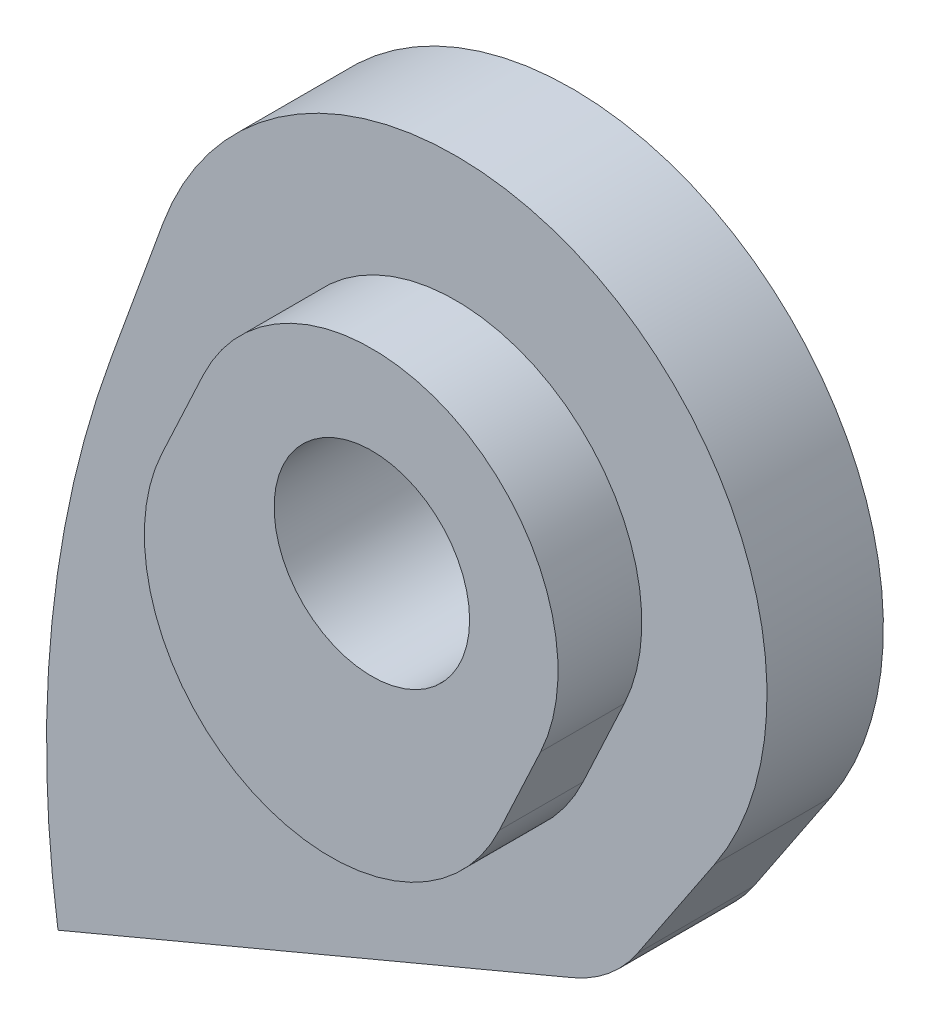
SolidWorks part; units mm, degrees
ref_plane "Front Plane" through (0, 0, 0) normal (0, 0, 1) x (1, 0, 0)
ref_plane "Top Plane" through (0, 0, 0) normal (0, 1, 0) x (1, 0, 0)
ref_plane "Right Plane" through (0, 0, 0) normal (1, 0, 0) x (0, 0, -1)
sketch "Sketch6" plane through (0, 0, 0) normal (0, 0, 1) x (1, 0, 0)
  line L0 (0, 0) -> (40.1809, 0) construction
  line L1 (0, 0) -> (35.507, 92.499) construction
  line L2 (19.3519, 50.4133) -> (0.4719, 63.0164) construction
  line L3 (19.3519, 50.4133) -> (-36.1025, 71.7003) construction
  dimension "D1" = 69
  dimension "D2" = 54
  dimension "D3" = 22.7
  dimension "D4" = 5
sketch "Sketch3" plane through (0, 0, 0) normal (0, 0, 1) x (1, 0, 0)
  line L0 (24.1743, 72.523) -> (120.8717, 72.523) construction
  line L6 (11.8164, 60.2529) -> (11.7284, 60.3116)
  line L7 (7.3748, 53.5992) -> (5.9136, 54.5745)
  line L8 (19.3519, 50.4133) -> (0.4719, 63.0164) construction
  line L9 (-6.1719, 82.4206) -> (-7.2903, 79.3479)
  line L10 (19.3519, 50.4133) -> (13.2479, 41.2693) construction
  line L11 (19.3519, 50.4133) -> (31.6629, 68.8558) construction
  line L12 (4.0204, 73.9337) -> (5.6789, 76.4182)
  line L14 (0.1147, 80.1325) -> (27.1455, 62.0885) construction
  line L15 (0.1147, 80.1325) -> (-7.2903, 79.3479) construction
  line L16 (0.1147, 80.1325) -> (0.1147, 91.1913) construction
  line L17 (0.1147, 80.1325) -> (-6.1719, 82.4206) construction
  arc A0 (13.4996, 47.0498) -> (20.2139, 57.1081) centre (19.3519, 50.4133) ccw
  arc A1 (20.2139, 57.1081) -> (11.8164, 60.2529) centre (22.7223, 76.5904) cw
  arc A2 (13.4996, 47.0498) -> (7.3748, 53.5992) centre (-3.5311, 37.2616) ccw
  arc A3 (11.7284, 60.3116) -> (6.8662, 65.9311) centre (19.4923, 71.9424) cw
  arc A4 (-6.1719, 82.4206) -> (5.6789, 76.4182) centre (0.1147, 80.1325) cw
  arc A5 (6.8662, 65.9311) -> (4.9012, 68.3908) centre (0.6246, 62.9595) ccw
  arc A6 (4.9012, 68.3908) -> (4.0204, 73.9337) centre (7.4585, 71.6386) cw
  arc A7 (5.9136, 54.5745) -> (0.4148, 56.2666) centre (0.3298, 46.2096) ccw
  arc A10 (0.4148, 56.2666) -> (-5.2798, 59.4837) centre (0.4719, 63.0164) cw
  circle A12 centre (19.3519, 50.4133) radius 2.75
  circle A13 centre (0.4719, 63.0164) radius 2.75
  circle A17 centre (0.1147, 80.1325) radius 2.1
  arc A18 (-7.2903, 79.3479) -> (-5.2798, 59.4837) centre (14.2795, 71.4971) ccw
  dimension "D1" = 5.5
  dimension "D2" = 5.5
  dimension "D3" = 4
  dimension "D5" = 4
  dimension "D6" = 4
  dimension "D4" = 4.2
  dimension "D17" = 70
  dimension "D18" = 3.27
  dimension "D14" = 6.69
  dimension "D7" = 3
  dimension "D8" = 4
  dimension "D9" = 3
  dimension "D10" = 4
  dimension "D11" = 19
  dimension "D12" = 19
  dimension "D13" = 22
  dimension "D15" = 32.5
  dimension "D16" = 14
extrude "Boss-Extrude2" add sketch "Sketch3" along normal blind 11
sketch "Sketch13" plane through (0, 0, 0) normal (0, 0, -1) x (-1, 0, 0)
  line L0 (-5.6789, 76.4182) -> (-4.0204, 73.9337)
  line L1 (-2.6258, 72.7829) -> (8.4277, 68.1397)
  line L2 (6.1719, 82.4206) -> (7.2903, 79.3479)
  arc A0 (-5.6789, 76.4182) -> (6.1719, 82.4206) centre (-0.1147, 80.1325) cw
  arc A1 (6.1719, 82.4206) -> (-5.6789, 76.4182) centre (-0.1147, 80.1325) ccw construction
  arc A2 (-4.0204, 73.9337) -> (-2.6258, 72.7829) centre (-1.4106, 75.6758) ccw
  arc A3 (5.2798, 59.4837) -> (7.2903, 79.3479) centre (-14.2795, 71.4971) ccw construction
  arc A4 (8.4277, 68.1397) -> (7.2903, 79.3479) centre (-14.2795, 71.4971) ccw
extrude "Boss-Extrude4" add sketch "Sketch13" along normal blind 2.5
sketch "Sketch12" plane through (0, 0, -2.5) normal (0, 0, -1) x (-1, 0, 0)
  line L0 (8.0136, 76.9658) -> (4.9242, 69.6114)
  line L4 (4.9242, 69.6114) -> (8.4277, 68.1397)
  line L5 (-2.6258, 72.7829) -> (8.4277, 68.1397) construction
  line L8 (-2.6258, 72.7829) -> (8.4277, 68.1397) construction
  arc A0 (8.0136, 76.9658) -> (8.4277, 68.1397) centre (-14.2795, 71.4971) cw
  arc A1 (5.2798, 59.4837) -> (8.4277, 68.1397) centre (-14.2795, 71.4971) ccw construction
  dimension "D1" = 3.8
  dimension "D2" = 90
extrude "Boss-Extrude3" add sketch "Sketch12" along normal blind 3
sketch "Sketch14" plane through (0, 0, 0) normal (0, 1, 0) x (1, 0, 0)
  line L0 (19.3519, 0) -> (-36.1025, 0) construction
  line L1 (-15.2308, 0) -> (32.0549, 0)
  line L2 (-15.2308, 0) -> (-15.2308, -12.5955)
  line L3 (-15.2308, -12.5955) -> (32.0549, -12.5955)
  line L4 (32.0549, 0) -> (32.0549, -12.5955)
extrude "Cut-Extrude1" cut sketch "Sketch14" along normal through all
sketch "Sketch16" plane through (0, 0, 0) normal (0, 0, 1) x (1, 0, 0)
  line L0 (0.1147, 80.1325) -> (-0.7728, 78.2293) construction
  line L1 (3.7399, 78.4421) -> (2.8524, 76.5388)
  line L2 (-3.5105, 81.823) -> (-4.398, 79.9198)
  line L3 (0.1147, 80.1325) -> (0.1147, 75.6752) construction
  arc A0 (3.7399, 78.4421) -> (-3.5105, 81.823) centre (0.1147, 80.1325) ccw
  arc A1 (-4.398, 79.9198) -> (2.8524, 76.5388) centre (-0.7728, 78.2293) ccw
  point P3 (-0.3291, 79.1809)
  dimension "D1" = 4
  dimension "D2" = 25
  dimension "D3" = 2.1
extrude "Boss-Extrude5" add sketch "Sketch16" along normal blind 1.8
sketch "Sketch15" plane through (0, 0, 1.8) normal (0, 0, 1) x (1, 0, 0)
  circle A0 centre (0.1147, 80.1325) radius 2.1
  dimension "D1" = 4.2
extrude "Cut-Extrude2" cut sketch "Sketch15" against normal through all
